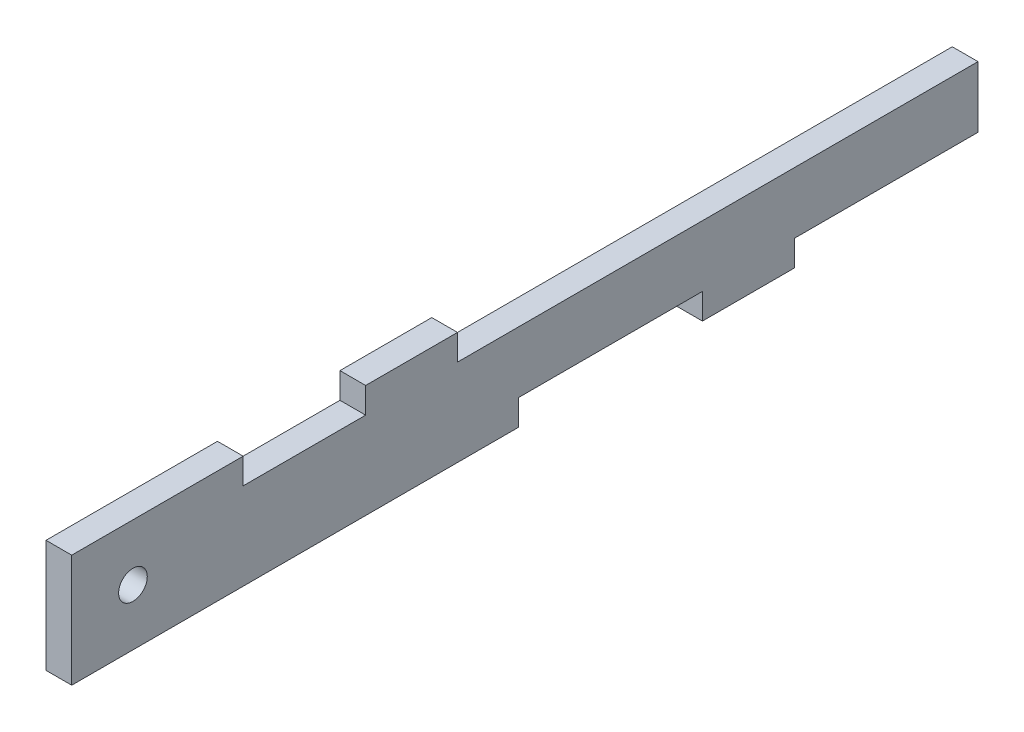
SolidWorks part; units mm, degrees
ref_plane "Front Plane" through (0, 0, 0) normal (0, 0, 1) x (1, 0, 0)
ref_plane "Top Plane" through (0, 0, 0) normal (0, 1, 0) x (1, 0, 0)
ref_plane "Right Plane" through (0, 0, 0) normal (1, 0, 0) x (0, 0, -1)
sketch "Sketch1" plane through (0, 0, 0) normal (1, 0, 0) x (0, 0, -1)
  line L1 (0, 0) -> (187.96, 0)
  line L2 (0, 0) -> (0, 23.368)
  line L3 (0, 23.368) -> (187.96, 23.368)
  line L4 (187.96, 0) -> (187.96, 23.368)
  dimension "D1" = 23.368
  dimension "D2" = 187.96
extrude "Base" add sketch "Sketch1" along normal blind 5.334
sketch "Sketch3" plane through (5.334, 0, 0) normal (1, 0, 0) x (0, 0, -1)
  line L0 (0, 0) -> (187.96, 0) construction
  line L2 (60.96, 18.034) -> (35.56, 18.034)
  line L3 (35.56, 18.034) -> (35.56, 23.368)
  line L4 (187.96, 23.368) -> (0, 23.368) construction
  line L5 (92.71, 0) -> (130.81, 0)
  line L6 (92.71, 0) -> (92.71, 5.334)
  line L7 (92.71, 5.334) -> (130.81, 5.334)
  line L8 (130.81, 0) -> (130.81, 5.334)
  line L10 (187.96, 0) -> (149.86, 0)
  line L11 (187.96, 0) -> (187.96, 5.334)
  line L12 (187.96, 5.334) -> (149.86, 5.334)
  line L13 (149.86, 0) -> (149.86, 5.334)
  line L14 (130.81, 5.334) -> (149.86, 5.334) construction
  line L15 (60.96, 18.034) -> (80.01, 18.034) construction
  line L16 (35.56, 23.368) -> (60.96, 23.368)
  line L19 (60.96, 23.368) -> (60.96, 18.034)
  line L20 (187.96, 23.368) -> (80.01, 23.368)
  line L21 (187.96, 23.368) -> (187.96, 18.034)
  line L22 (187.96, 18.034) -> (80.01, 18.034)
  line L23 (80.01, 23.368) -> (80.01, 18.034)
  dimension "D1" = 19.05
  dimension "D2" = 5.334
  dimension "D3" = 19.05
  dimension "D4" = 107.95
  dimension "D5" = 38.1
  dimension "D6" = 25.4
extrude "Tabs" cut sketch "Sketch3" against normal through all
sketch "Sketch4" plane through (5.334, 0, 0) normal (1, 0, 0) x (0, 0, -1)
  line L0 (0, 23.368) -> (0, 0) construction
  line L2 (35.56, 23.368) -> (0, 23.368) construction
  circle A0 centre (12.7, 11.684) radius 2.9718
  point P2 (0, 11.684)
  dimension "D1" = 5.9436
  dimension "D2" = 12.7
  dimension "D3" = 11.684
extrude "Axle" cut sketch "Sketch4" against normal through all
equation "\"material\"= \"gmaterial@full.assembly\""
equation "\"D1@Sketch1\"=(2*\"material\")+0.5"
equation "\"D2@Sketch3\"=\"material\""
equation "\"D3@Sketch4\"=\"material\"+0.25"
equation "\"D1@Base\"=\"material\""
